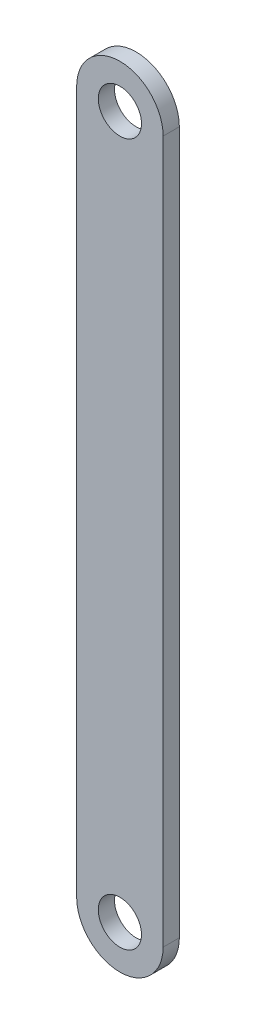
SolidWorks part; units mm, degrees
ref_plane "Front Plane" through (0, 0, 0) normal (0, 0, 1) x (1, 0, 0)
ref_plane "Top Plane" through (0, 0, 0) normal (0, 1, 0) x (1, 0, 0)
ref_plane "Right Plane" through (0, 0, 0) normal (1, 0, 0) x (0, 0, -1)
sketch "Sketch1" plane through (0, 0, 0) normal (0, 0, 1) x (1, 0, 0)
  line L0 (-12.5882, 0) -> (-12.5882, -65)
  line L1 (-4.5882, 0) -> (-4.5882, -65)
  arc A0 (-12.5882, 0) -> (-4.5882, 0) centre (-8.5882, 0) cw
  arc A1 (-12.5882, -65) -> (-4.5882, -65) centre (-8.5882, -65) ccw
  dimension "D1" = 4
  dimension "D3" = 4
  dimension "D2" = 65
extrude "Boss-Extrude1" add sketch "Sketch1" along normal blind 1.5
sketch "Sketch2" plane through (0, 0, 1.5) normal (0, 0, 1) x (1, 0, 0)
  circle A0 centre (-8.5882, 0) radius 2
  circle A1 centre (-8.5882, -65) radius 2
  dimension "D1" = 4
  dimension "D2" = 4
extrude "Cut-Extrude1" cut sketch "Sketch2" against normal blind 2
